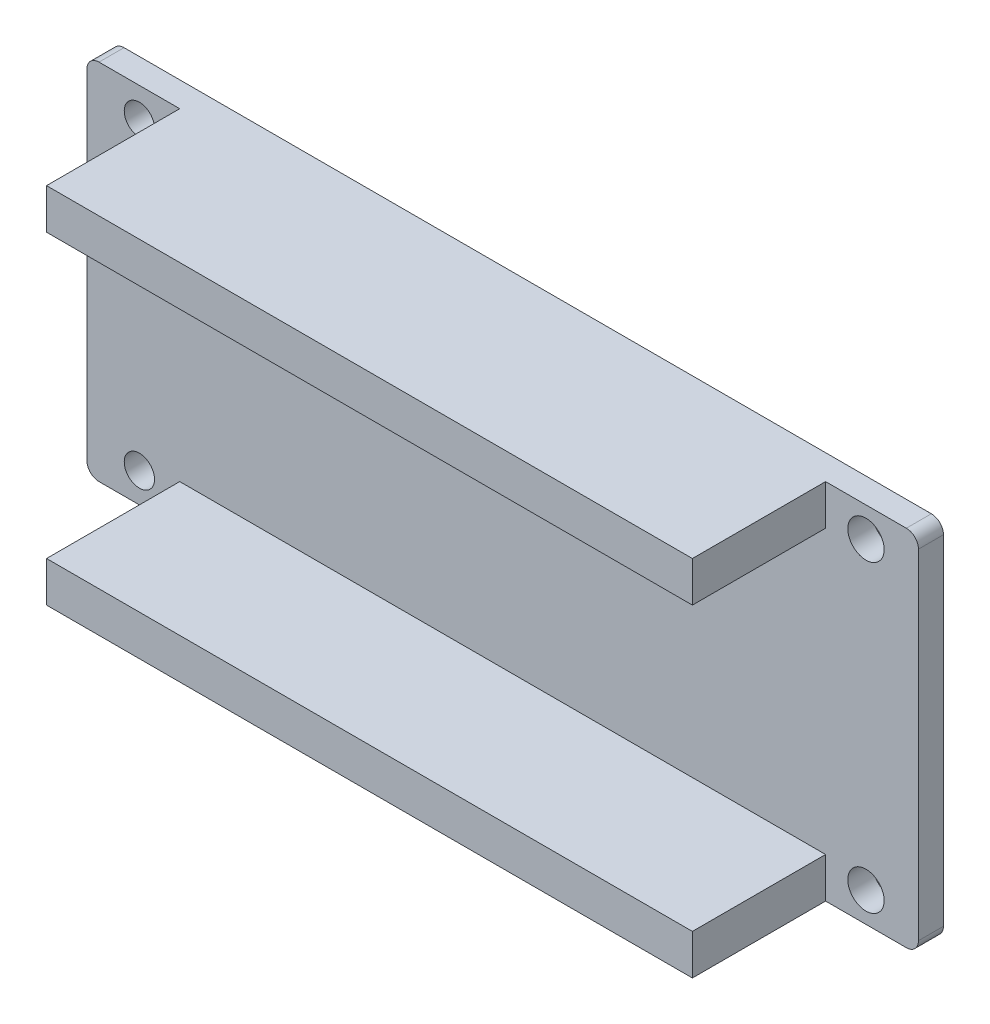
SolidWorks part; units mm, degrees
ref_plane "Front Plane" through (0, 0, 0) normal (0, 0, 1) x (1, 0, 0)
ref_plane "Top Plane" through (0, 0, 0) normal (0, 1, 0) x (1, 0, 0)
ref_plane "Right Plane" through (0, 0, 0) normal (1, 0, 0) x (0, 0, -1)
sketch "Sketch1" plane through (0, 0, 0) normal (0, 0, 1) x (1, 0, 0)
  line L1 (0, 0) -> (52.324, 0)
  line L2 (0, 0) -> (0, 22.86)
  line L3 (0, 22.86) -> (52.324, 22.86)
  line L4 (52.324, 0) -> (52.324, 22.86)
  dimension "D1" = 22.86
  dimension "D2" = 52.324
extrude "Boss-Extrude1" add sketch "Sketch1" along normal blind 1.5748
sketch "Sketch2" plane through (0, 0, 0) normal (0, 0, -1) x (-1, 0, 0)
  line L0 (0, 11.43) -> (-52.324, 11.43) construction
  line L1 (0, 22.86) -> (0, 0) construction
  line L2 (-52.324, 0) -> (-52.324, 22.86) construction
  line L4 (-43.688, 2.54) -> (-12.7, 2.54)
  line L5 (-43.688, 2.54) -> (-43.688, 20.32)
  line L6 (-43.688, 20.32) -> (-12.7, 20.32)
  line L7 (-12.7, 2.54) -> (-12.7, 20.32)
  line L8 (-43.688, 2.54) -> (-12.7, 20.32) construction
  line L9 (-43.688, 20.32) -> (-12.7, 2.54) construction
  point P7 (-28.194, 11.43)
  dimension "D1" = 17.78
  dimension "D2" = 30.988
  dimension "D3" = 8.636
extrude "Boss-Extrude2" add sketch "Sketch2" along normal blind 2.032
sketch "Sketch3" plane through (0, 0, 1.5748) normal (0, 0, 1) x (1, 0, 0)
  line L0 (52.324, 11.43) -> (0, 11.43) construction
  line L1 (52.324, 0) -> (52.324, 22.86) construction
  line L2 (0, 22.86) -> (0, 0) construction
  line L3 (52.324, 22.86) -> (0, 22.86) construction
  line L4 (5.842, 22.86) -> (46.482, 22.86)
  line L5 (5.842, 22.86) -> (5.842, 20.32)
  line L6 (5.842, 20.32) -> (46.482, 20.32)
  line L7 (46.482, 22.86) -> (46.482, 20.32)
  line L8 (26.162, 11.43) -> (26.162, 34.29) construction
  line L9 (5.842, 2.54) -> (46.482, 2.54)
  line L10 (46.482, 0) -> (46.482, 2.54)
  line L11 (5.842, 0) -> (46.482, 0)
  line L12 (5.842, 0) -> (5.842, 2.54)
  point P14 (26.162, 22.86)
  dimension "D1" = 40.64
  dimension "D2" = 2.54
extrude "Boss-Extrude3" add sketch "Sketch3" along normal blind 8.382
fillet "Fillet1" radius 0.762 4 edges at (0, 0, 0.7874) (52.324, 0, 0.7874) (52.324, 22.86, 0.7874) (0, 22.86, 0.7874)
sketch "Sketch4" plane through (0, 0, 0) normal (0, 0, -1) x (-1, 0, 0)
  line L0 (-52.324, 11.43) -> (0, 11.43) construction
  line L1 (-52.324, 0.762) -> (-52.324, 22.098) construction
  line L2 (0, 22.098) -> (0, 0.762) construction
  line L3 (-49.022, 20.9931) -> (-3.302, 20.9931) construction
  line L4 (-49.022, 1.8669) -> (-3.302, 1.8669) construction
  circle A0 centre (-49.022, 20.9931) radius 1.143
  circle A1 centre (-3.302, 20.9931) radius 0.9525
  circle A2 centre (-3.302, 1.8669) radius 0.9525
  circle A3 centre (-49.022, 1.8669) radius 1.143
  point P10 (-26.162, 20.9931)
  point P11 (-26.162, 11.43)
  point P12 (-3.302, 21.4892)
  point P13 (-3.302, 20.8644)
  dimension "D1" = 2.286
  dimension "D2" = 1.905
  dimension "D3" = 45.72
  dimension "D4" = 19.1262
extrude "Cut-Extrude1" cut sketch "Sketch4" against normal up to surface (1.5748 mm away) up to face at (26.162, 11.43, 1.5748)
